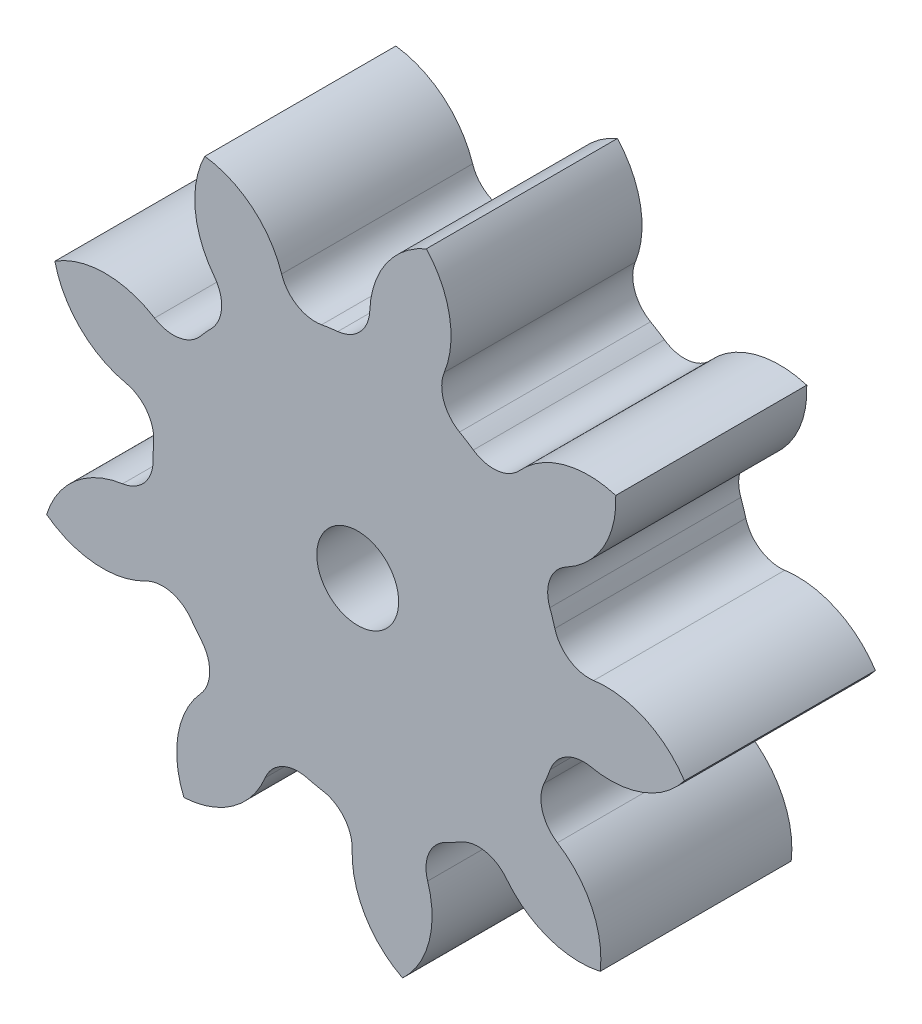
SolidWorks part; units mm, degrees
ref_plane "Alzado" through (0, 0, 0) normal (1, 0, 0) x (0, 1, 0)
ref_plane "Planta" through (0, 0, 0) normal (0, 0, 1) x (0, 1, 0)
ref_plane "Vista lateral" through (0, 0, 0) normal (0, 1, 0) x (-1, 0, 0)
sketch "Croquis1" plane through (0, 0, 0) normal (0, 0, 1) x (0, 1, 0)
  circle A0 centre (0, 0) radius 1.5
  circle A1 centre (0, 0) radius 3
  circle A2 centre (0, 0) radius 10
  circle A3 centre (0, 0) radius 12
extrude "Saliente-Extruir1" add sketch "Croquis1" along normal blind 7 contours A3 A2 | A1 A0 | A2 A1 | A0
sketch "Croquis2" plane through (0, 0, 0) normal (0, 0, -1) x (-1, 0, 0)
  arc A1 (-1.6717, -11.883) -> (6.4038, -10.1484) centre (0, 0) ccw
  arc A2 (1.2814, -7.3897) -> (1.8661, -7.2641) centre (0, 0) ccw
  arc A3 (-1.6717, -11.883) -> (0.2043, -8.7146) centre (-3.2139, -8.8302) ccw
  arc A4 (6.4038, -10.1484) -> (3.3922, -8.0298) centre (6.5565, -6.7316) cw
  arc A5 (0.2043, -8.7146) -> (1.2814, -7.3897) centre (1.5036, -8.6706) cw
  arc A6 (3.3922, -8.0298) -> (1.8661, -7.2641) centre (2.1895, -8.5233) ccw
  dimension "D1" = 1.3
extrude "Cortar-Extruir2" cut sketch "Croquis2" against normal blind 7
pattern_circular "MatrizC2" count 9 every 40 about axis through (0, 0, 0) along (0, 0, 1) of "Cortar-Extruir2"
sketch "Croquis3" plane through (0, 0, 0) normal (0, 0, -1) x (-1, 0, 0)
  circle A0 centre (0, 0) radius 1.5
extrude "Cortar-Extruir3" cut sketch "Croquis3" against normal blind 7
sketch "Croquis7" plane through (0, 0, 0) normal (0, 0, -1) x (-1, 0, 0)
  circle A0 centre (0, 0) radius 3
extrude "Cortar-Extruir4" cut sketch "Croquis7" against normal blind 4.5
